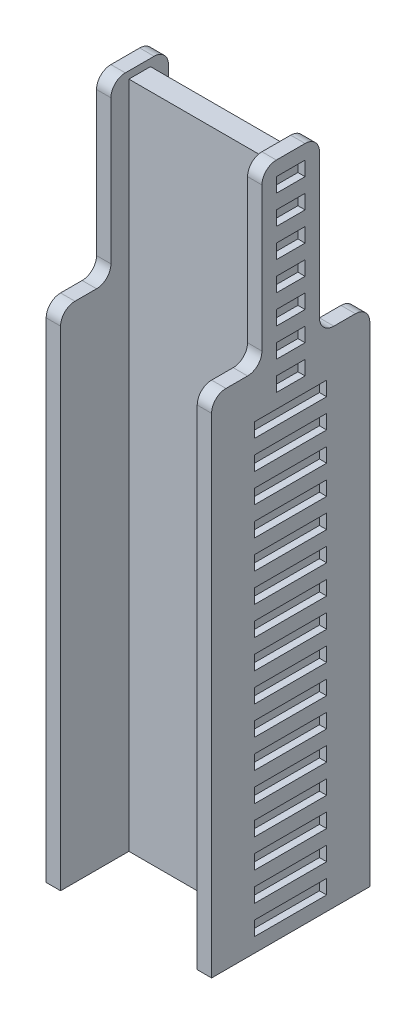
SolidWorks part; units mm, degrees
ref_plane "Front Plane" through (0, 0, 0) normal (0, 0, 1) x (1, 0, 0)
ref_plane "Top Plane" through (0, 0, 0) normal (0, 1, 0) x (1, 0, 0)
ref_plane "Right Plane" through (0, 0, 0) normal (1, 0, 0) x (0, 0, -1)
sketch "Sketch2" plane through (0, 0, 0) normal (0, 1, 0) x (1, 0, 0)
  line L0 (-5.75, 1.25) -> (-5.75, -2.75)
  line L1 (-5.75, -2.75) -> (-4.75, -2.75)
  line L2 (-4.75, -2.75) -> (-4.75, -1.5)
  line L3 (-4.75, -1.5) -> (4.75, -1.5)
  line L4 (4.75, -1.5) -> (4.75, -2.75)
  line L5 (4.75, -2.75) -> (5.75, -2.75)
  line L6 (5.75, -2.75) -> (5.75, 1.25)
  line L7 (5.75, 1.25) -> (4.75, 1.25)
  line L8 (4.75, 1.25) -> (4.75, 0)
  line L9 (4.75, 0) -> (-4.75, 0)
  line L10 (-4.75, 0) -> (-4.75, 1.25)
  line L11 (-4.75, 1.25) -> (-5.75, 1.25)
  point P2 (0, 0)
  dimension "D1" = 9.5
  dimension "D2" = 4
  dimension "D3" = 1
  dimension "D4" = 4
  dimension "D5" = 1
  dimension "D6" = 1.5
  dimension "D7" = 1.25
  dimension "D8" = 1.25
extrude "Boss-Extrude1" add sketch "Sketch2" along normal blind 12
sketch "Sketch3" plane through (0, 12, 0) normal (0, 1, 0) x (1, 0, 0)
  line L0 (4.75, 0) -> (-4.75, 0) construction
  line L1 (-4.75, -1.5) -> (4.75, -1.5) construction
  line L2 (4.75, 0) -> (-4.75, 0)
  line L3 (-4.75, -1.5) -> (4.75, -1.5)
  line L4 (-4.75, 0) -> (-4.75, -1.5)
  line L5 (4.75, -1.5) -> (4.75, 0)
extrude "Cut-Extrude1" cut sketch "Sketch3" against normal blind 0.5
sketch "Sketch4" plane through (0, 0, 0) normal (0, -1, 0) x (1, 0, 0)
  line L0 (4.75, 0) -> (-4.75, 0) construction
  line L1 (-4.75, 1.5) -> (4.75, 1.5) construction
  line L2 (4.75, 0) -> (-4.75, 0)
  line L3 (-4.75, 1.5) -> (4.75, 1.5)
  line L4 (-4.75, 1.5) -> (-4.75, 6.25)
  line L5 (-4.75, 6.25) -> (-5.75, 6.25)
  line L6 (-5.75, 6.25) -> (-5.75, -4.75)
  line L7 (-5.75, -4.75) -> (-4.75, -4.75)
  line L8 (-4.75, -4.75) -> (-4.75, 0)
  line L9 (4.75, 0) -> (4.75, -4.75)
  line L10 (4.75, -4.75) -> (5.75, -4.75)
  line L11 (5.75, -4.75) -> (5.75, 6.25)
  line L12 (5.75, 6.25) -> (4.75, 6.25)
  line L13 (4.75, 6.25) -> (4.75, 1.5)
  line L14 (-5.75, -1.25) -> (-5.75, 2.75) construction
  line L15 (5.75, 2.75) -> (5.75, -1.25) construction
  point P16 (-5.75, 5.6816)
  dimension "D1" = 11
  dimension "D2" = 6.25
extrude "Boss-Extrude2" add sketch "Sketch4" along normal blind 5
fillet "Fillet1" radius 1 12 edges at (5.25, 0, 6.25) (-5.25, 0, 6.25) (5.25, 0, -4.75) (-5.25, 0, -4.75) (5.25, 12, -1.25) (5.25, 12, 2.75) (-5.25, 12, 2.75) (-5.25, 12, -1.25) (-5.25, 0, -1.25) (5.25, 0, -1.25) (-5.25, 0, 2.75) (5.25, 0, 2.75)
sketch "Sketch5" plane through (0, -5, 0) normal (0, -1, 0) x (1, 0, 0)
  line L12 (4.75, 0) -> (4.75, -4.75)
  line L13 (4.75, -4.75) -> (5.75, -4.75)
  line L14 (5.75, -4.75) -> (5.75, 6.25)
  line L15 (5.75, 6.25) -> (4.75, 6.25)
  line L16 (4.75, 6.25) -> (4.75, 1.5)
  line L17 (4.75, 1.5) -> (-4.75, 1.5)
  line L18 (-4.75, 1.5) -> (-4.75, 6.25)
  line L19 (-4.75, 6.25) -> (-5.75, 6.25)
  line L20 (-5.75, 6.25) -> (-5.75, -4.75)
  line L21 (-5.75, -4.75) -> (-4.75, -4.75)
  line L22 (-4.75, -4.75) -> (-4.75, 0)
  line L23 (-4.75, 0) -> (4.75, 0)
  line L24 (4.75, 0) -> (4.75, -4.75)
  line L25 (4.75, -4.75) -> (5.75, -4.75)
  line L26 (5.75, -4.75) -> (5.75, 6.25)
  line L27 (5.75, 6.25) -> (4.75, 6.25)
  line L28 (4.75, 6.25) -> (4.75, 1.5)
  line L29 (4.75, 1.5) -> (-4.75, 1.5)
  line L30 (-4.75, 1.5) -> (-4.75, 6.25)
  line L31 (-4.75, 6.25) -> (-5.75, 6.25)
  line L32 (-5.75, 6.25) -> (-5.75, -4.75)
  line L33 (-5.75, -4.75) -> (-4.75, -4.75)
  line L34 (-4.75, -4.75) -> (-4.75, 0)
  line L35 (-4.75, 0) -> (4.75, 0)
  dimension "D1" = 0
extrude "Boss-Extrude3" add sketch "Sketch5" along normal blind 30
sketch "Sketch6" plane through (-5.75, 0, 0) normal (-1, 0, 0) x (0, 0, 1)
  line L0 (-0.25, 12) -> (1.75, 12) construction
  line L1 (-1.75, -3) -> (3.25, -3)
  line L2 (-1.75, -3) -> (-1.75, -4)
  line L3 (-1.75, -4) -> (3.25, -4)
  line L4 (3.25, -3) -> (3.25, -4)
  line L9 (-1.75, -5) -> (3.25, -5)
  line L10 (-1.75, -5) -> (-1.75, -6)
  line L11 (3.25, -5) -> (3.25, -6)
  line L12 (-1.75, -6) -> (3.25, -6)
  line L13 (-1.75, -7) -> (3.25, -7)
  line L14 (-1.75, -7) -> (-1.75, -8)
  line L15 (3.25, -7) -> (3.25, -8)
  line L16 (-1.75, -8) -> (3.25, -8)
  line L17 (-1.75, -9) -> (3.25, -9)
  line L18 (-1.75, -9) -> (-1.75, -10)
  line L19 (3.25, -9) -> (3.25, -10)
  line L20 (-1.75, -10) -> (3.25, -10)
  line L21 (-1.75, -11) -> (3.25, -11)
  line L22 (-1.75, -11) -> (-1.75, -12)
  line L23 (3.25, -11) -> (3.25, -12)
  line L24 (-1.75, -12) -> (3.25, -12)
  line L25 (-1.75, -13) -> (3.25, -13)
  line L26 (-1.75, -13) -> (-1.75, -14)
  line L27 (3.25, -13) -> (3.25, -14)
  line L28 (-1.75, -14) -> (3.25, -14)
  line L29 (-1.75, -15) -> (3.25, -15)
  line L30 (-1.75, -15) -> (-1.75, -16)
  line L31 (3.25, -15) -> (3.25, -16)
  line L32 (-1.75, -16) -> (3.25, -16)
  line L33 (-1.75, -17) -> (3.25, -17)
  line L34 (-1.75, -17) -> (-1.75, -18)
  line L35 (3.25, -17) -> (3.25, -18)
  line L36 (-1.75, -18) -> (3.25, -18)
  line L37 (-1.75, -19) -> (3.25, -19)
  line L38 (-1.75, -19) -> (-1.75, -20)
  line L39 (3.25, -19) -> (3.25, -20)
  line L40 (-1.75, -20) -> (3.25, -20)
  line L41 (-1.75, -21) -> (3.25, -21)
  line L42 (-1.75, -21) -> (-1.75, -22)
  line L43 (3.25, -21) -> (3.25, -22)
  line L44 (-1.75, -22) -> (3.25, -22)
  line L45 (-1.75, -23) -> (3.25, -23)
  line L46 (-1.75, -23) -> (-1.75, -24)
  line L47 (3.25, -23) -> (3.25, -24)
  line L48 (-1.75, -24) -> (3.25, -24)
  line L49 (-1.75, -25) -> (3.25, -25)
  line L50 (-1.75, -25) -> (-1.75, -26)
  line L51 (3.25, -25) -> (3.25, -26)
  line L52 (-1.75, -26) -> (3.25, -26)
  line L53 (-1.75, -27) -> (3.25, -27)
  line L54 (-1.75, -27) -> (-1.75, -28)
  line L55 (3.25, -27) -> (3.25, -28)
  line L56 (-1.75, -28) -> (3.25, -28)
  line L57 (-1.75, -29) -> (3.25, -29)
  line L58 (-1.75, -29) -> (-1.75, -30)
  line L59 (3.25, -29) -> (3.25, -30)
  line L60 (-1.75, -30) -> (3.25, -30)
  line L61 (-1.75, -31) -> (3.25, -31)
  line L62 (-1.75, -31) -> (-1.75, -32)
  line L63 (3.25, -31) -> (3.25, -32)
  line L64 (-1.75, -32) -> (3.25, -32)
  line L65 (-1.75, -33) -> (3.25, -33)
  line L66 (-1.75, -33) -> (-1.75, -34)
  line L67 (3.25, -33) -> (3.25, -34)
  line L68 (-1.75, -34) -> (3.25, -34)
  line L69 (-0.25, 1) -> (-0.25, 0)
  line L70 (-0.25, -1) -> (1.75, -1)
  line L71 (-0.25, -1) -> (-0.25, -2)
  line L72 (-0.25, -2) -> (1.75, -2)
  line L73 (1.75, -1) -> (1.75, -2)
  line L74 (-0.25, 1) -> (1.75, 1)
  line L75 (1.75, 1) -> (1.75, 0)
  line L76 (-0.25, 0) -> (1.75, 0)
  line L77 (-0.25, 3) -> (-0.25, 2)
  line L78 (-0.25, 3) -> (1.75, 3)
  line L79 (1.75, 3) -> (1.75, 2)
  line L80 (-0.25, 2) -> (1.75, 2)
  line L81 (-0.25, 5) -> (-0.25, 4)
  line L82 (-0.25, 5) -> (1.75, 5)
  line L83 (1.75, 5) -> (1.75, 4)
  line L84 (-0.25, 4) -> (1.75, 4)
  line L85 (-0.25, 7) -> (-0.25, 6)
  line L86 (-0.25, 7) -> (1.75, 7)
  line L87 (1.75, 7) -> (1.75, 6)
  line L88 (-0.25, 6) -> (1.75, 6)
  line L89 (-0.25, 9) -> (-0.25, 8)
  line L90 (-0.25, 9) -> (1.75, 9)
  line L91 (1.75, 9) -> (1.75, 8)
  line L92 (-0.25, 8) -> (1.75, 8)
  line L93 (-0.25, 11) -> (-0.25, 10)
  line L94 (-0.25, 11) -> (1.75, 11)
  line L95 (1.75, 11) -> (1.75, 10)
  line L96 (-0.25, 10) -> (1.75, 10)
  point P4 (0.75, -3)
  point P7 (0.75, 12)
  point P8 (0.75, -1)
  point P9 (0.75, -4)
  dimension "D1" = 1
  dimension "D2" = 5
  dimension "D3" = 15
  dimension "D5" = 1
  dimension "D6" = 1
  dimension "D7" = 2
  dimension "D8" = 1
  dimension "D10" = 1
  dimension "D4" = 16
  dimension "D9" = 7
extrude "Cut-Extrude2" cut sketch "Sketch6" against normal blind 0.5
mirror "Mirror1" about plane through (0, 0, 0) normal (1, 0, 0) of "Cut-Extrude2"
